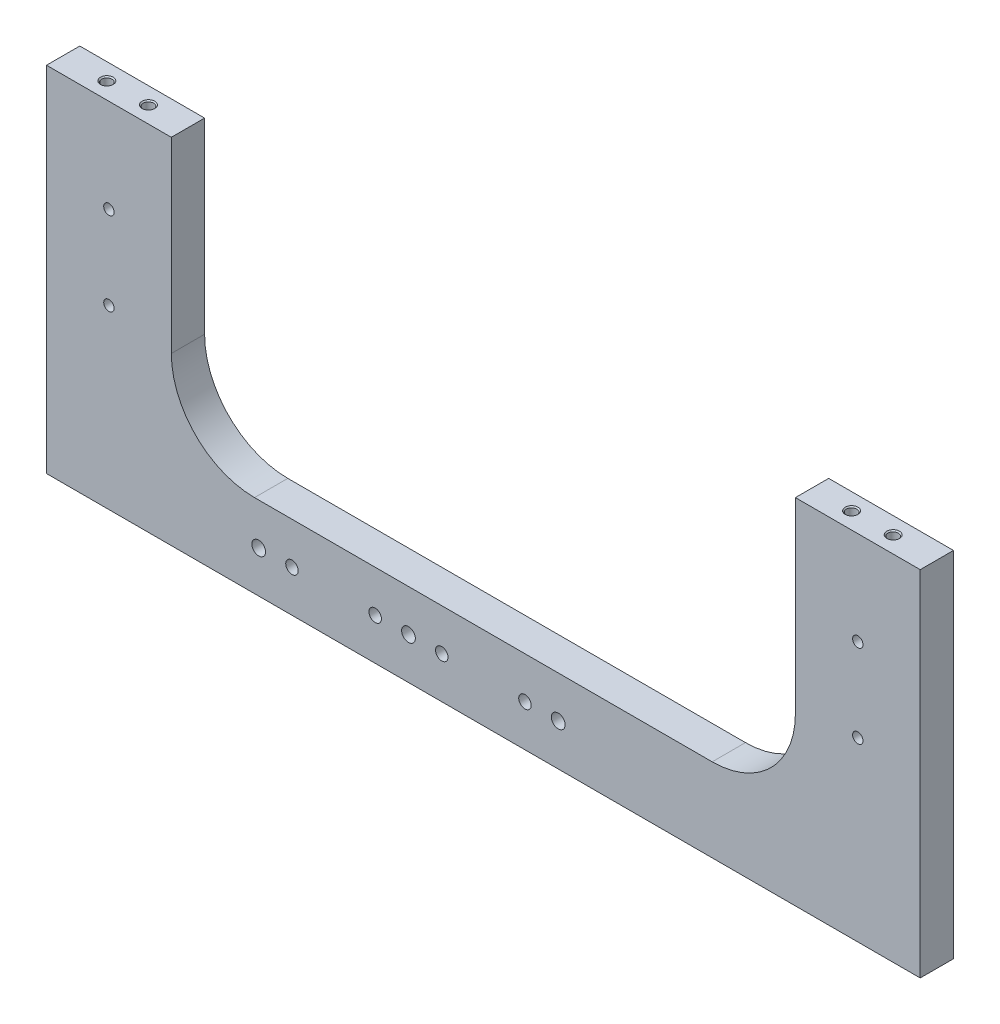
SolidWorks part; units mm, degrees
ref_plane "Front Plane" through (0, 0, 0) normal (0, 0, 1) x (1, 0, 0)
ref_plane "Top Plane" through (0, 0, 0) normal (0, 1, 0) x (1, 0, 0)
ref_plane "Right Plane" through (0, 0, 0) normal (1, 0, 0) x (0, 0, -1)
sketch "Skizze1" plane through (0, 0, 0) normal (0, 0, 1) x (1, 0, 0)
  line L1 (-105, 42.5) -> (105, 42.5)
  line L2 (-105, 42.5) -> (-105, -42.5)
  line L3 (-105, -42.5) -> (105, -42.5)
  line L4 (105, 42.5) -> (105, -42.5)
  line L5 (0, -42.5) -> (0, 42.5) construction
  line L6 (-105, 0) -> (105, 0) construction
  point P176 (0, 0)
  dimension "D1" = 210
  dimension "D2" = 85
extrude "Aufsatz-Linear austragen1" add sketch "Skizze1" along normal blind 8
hole_wizard "M3 Gewindebohrung1" positions "Skizze2" profile "Skizze3" tap size "M3" standard "DIN"
sketch "Skizze2" plane through (0, 42.5, 0) normal (0, 1, 0) x (1, 0, 0)
  line L0 (-105, -4) -> (105, -4) construction
  line L1 (-105, -8) -> (-105, 0) construction
  line L2 (105, -8) -> (105, 0) construction
  line L5 (0, 0) -> (0, -8) construction
  line L6 (105, 0) -> (-105, 0) construction
  line L7 (105, -8) -> (-105, -8) construction
  line L10 (-89.5, 0) -> (-89.5, -8) construction
  line L12 (89.5, 0) -> (89.5, -8) construction
  point P0 (-94.5, -4)
  point P26 (-84.5, -4)
  point P29 (84.5, -4)
  point P30 (94.5, -4)
  dimension "D1" = 10
  dimension "D2" = 179
cosmetic thread "Bohrungsgewinde1" parameters "D1"=4, "D2"=3
cosmetic thread "Bohrungsgewinde2" parameters "D1"=4, "D2"=3
cosmetic thread "Bohrungsgewinde3" parameters "D1"=4, "D2"=3
cosmetic thread "Bohrungsgewinde4" parameters "D1"=4, "D2"=3
sketch "Skizze3" plane through (-94.5, 42.5, 4) normal (1, 0, 0) x (0, 0, 1)
  line L0 (0, 0) -> (0, 9.2511)
  line L1 (0, 9.2511) -> (1.25, 8.5)
  line L2 (1.25, 8.5) -> (1.25, 0.275)
  line L3 (1.25, 0.275) -> (1.525, 0)
  line L5 (1.525, 0) -> (0, 0)
  line L6 (-1.25, 0.275) -> (-1.525, 0) construction
  line L10 (0, 9.2511) -> (-1.25, 8.5) construction
  line L11 (0, -6.35) -> (0, 107.95) construction
  dimension "Bohrerdurchmesser" = 2.5
  dimension "Bohrungstiefe" = 8.5
  dimension "Senkdurchmesser (Oben)" = 3.05
  dimension "Senkwinkel (Oben)" = 90
  dimension "Spitzenwinkel" = 118
sketch "Skizze4" plane through (0, 0, 8) normal (0, 0, 1) x (1, 0, 0)
  line L0 (105, 42.5) -> (-105, 42.5) construction
  line L1 (-75, 42.5) -> (75, 42.5)
  line L2 (-75, 42.5) -> (-75, -22.5)
  line L3 (-75, -22.5) -> (75, -22.5)
  line L4 (75, 42.5) -> (75, -22.5)
  line L5 (0, -22.5) -> (0, 42.5) construction
  line L6 (-75, 10) -> (75, 10) construction
  line L7 (-105, 42.5) -> (-105, -42.5) construction
  line L8 (105, -42.5) -> (105, 42.5) construction
  line L9 (-105, -42.5) -> (105, -42.5) construction
  point P280 (0, 10)
  dimension "D1" = 30
  dimension "D2" = 20
extrude "Schnitt-Linear austragen1" cut sketch "Skizze4" against normal blind 8
fillet "Verrundung1" radius 20 2 edges at (75, -22.5, 4) (-75, -22.5, 4)
hole_wizard "Ø3.0 (3) Durchmesser Bohrung1" positions "Skizze5" profile "Skizze6" hole size "Ø3.0" standard "DIN" end condition through all
sketch "Skizze5" plane through (0, 0, 8) normal (0, 0, 1) x (1, 0, 0)
  line L0 (0, -22.5) -> (0, -42.5) construction
  line L1 (-55, -22.5) -> (55, -22.5) construction
  line L2 (-105, -42.5) -> (105, -42.5) construction
  point P0 (-10, -32.5)
  point P11 (10, -32.5)
  dimension "D1" = 20
  dimension "D2" = 10
sketch "Skizze6" plane through (-10, -32.5, 8) normal (1, 0, 0) x (0, -1, 0)
  line L0 (0, 0) -> (0, 8)
  line L1 (0, 8) -> (1.5, 8)
  line L2 (1.5, 8) -> (1.5, 0)
  line L5 (1.5, 0) -> (0, 0)
  line L11 (0, -6.35) -> (0, 107.95) construction
  dimension "Bohrerdurchmesser" = 3
  dimension "Bohrungstiefe" = 8
hole_wizard "M4 Gewindebohrung1" positions "Skizze7" profile "Skizze8" tap size "M4" standard "DIN" end condition through all
sketch "Skizze7" plane through (0, 0, 8) normal (0, 0, 1) x (1, 0, 0)
  line L0 (0, -22.5) -> (0, -42.5) construction
  line L1 (-55, -22.5) -> (55, -22.5) construction
  line L2 (-105, -42.5) -> (105, -42.5) construction
  line L4 (10, -32.5) -> (-10, -32.5) construction
  line L5 (-10, -32.5) -> (-18, -32.5) construction
  point P0 (-18, -32.5)
  point P18 (18, -32.5)
  dimension "D1" = 36
sketch "Skizze8" plane through (-18, -32.5, 8) normal (1, 0, 0) x (0, -1, 0)
  line L0 (0, 0) -> (0, 8)
  line L1 (0, 8) -> (1.65, 8)
  line L2 (1.65, 8) -> (1.65, 0)
  line L5 (1.65, 0) -> (0, 0)
  line L11 (0, -6.35) -> (0, 107.95) construction
  dimension "Bohrerdurchmesser" = 3.3
  dimension "Bohrungstiefe" = 8
cosmetic thread "Bohrungsgewinde5" parameters "D2"=4
cosmetic thread "Bohrungsgewinde6" parameters "D2"=4
pattern_linear "Lineares Muster1" count 2 spacing 36 along (-1, 0, 0) of "M4 Gewindebohrung1", "Ø3.0 (3) Durchmesser Bohrung1"
hole_wizard "M3 Gewindebohrung2" positions "Skizze9" profile "Skizze10" tap size "M3" standard "DIN"
sketch "Skizze9" plane through (0, 0, 8) normal (0, 0, 1) x (1, 0, 0)
  line L0 (-90, 42.5) -> (-90, -42.5) construction
  line L1 (-75, 42.5) -> (-105, 42.5) construction
  line L2 (-105, -42.5) -> (105, -42.5) construction
  line L4 (0, -42.5) -> (0, -22.5) construction
  line L5 (-55, -22.5) -> (55, -22.5) construction
  point P0 (-90, 20)
  point P2 (-90, 0)
  point P23 (90, 0)
  point P24 (90, 20)
  dimension "D1" = 20
sketch "Skizze10" plane through (-90, 20, 8) normal (1, 0, 0) x (0, -1, 0)
  line L0 (0, 0) -> (0, 9.2511)
  line L1 (0, 9.2511) -> (1.25, 8.5)
  line L2 (1.25, 8.5) -> (1.25, 0)
  line L5 (1.25, 0) -> (0, 0)
  line L10 (0, 9.2511) -> (-1.25, 8.5) construction
  line L11 (0, -6.35) -> (0, 107.95) construction
  dimension "Bohrerdurchmesser" = 2.5
  dimension "Bohrungstiefe" = 8.5
  dimension "Spitzenwinkel" = 118
cosmetic thread "Bohrungsgewinde7" parameters "D1"=6, "D2"=3
cosmetic thread "Bohrungsgewinde8" parameters "D1"=6, "D2"=3
cosmetic thread "Bohrungsgewinde9" parameters "D1"=6, "D2"=3
cosmetic thread "Bohrungsgewinde10" parameters "D1"=6, "D2"=3
